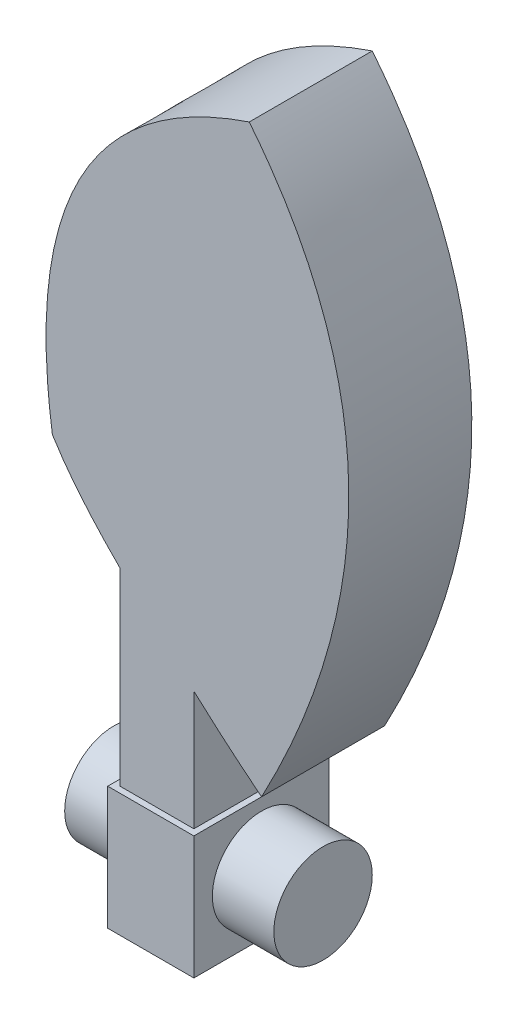
SolidWorks part; units mm, degrees
ref_plane "Front Plane" through (0, 0, 0) normal (0, 0, 1) x (1, 0, 0)
ref_plane "Top Plane" through (0, 0, 0) normal (0, 1, 0) x (1, 0, 0)
ref_plane "Right Plane" through (0, 0, 0) normal (1, 0, 0) x (0, 0, -1)
sketch "Sketch1" plane through (0, 0, 0) normal (0, 0, 1) x (1, 0, 0)
  spline S0 degree 2 poles (0, 0) (-3.4196, 23.4679) (16, 30) knots 0 0 0 1 1 1
  spline S1 degree 2 poles (16, 30) (31.6649, 10.4933) (17, -17) knots 0 0 0 1 1 1
  spline S2 degree 3 poles (0, 0) (2.2841, -3.7298) (8.7796, -9.7925) (13.5207, -14.2233) (17, -17) knots 0 0 0 0 0.559197 1 1 1 1
  dimension "D1" = 6
  dimension "D2" = 3
  dimension "D3" = 8
  dimension "D4" = 4
  dimension "D5" = 6
  dimension "D6" = 7
  dimension "D7" = 5.8243
  dimension "D8" = 16
  dimension "D9" = 20
  dimension "D10" = 24
  dimension "D11" = 30
extrude "Boss-Extrude1" add sketch "Sketch1" along normal blind 10
ref_plane "Plane2" through (0, -32, 0) normal (0, 1, 0) x (1, 0, 0)
sketch "Sketch5" plane through (0, -32, 0) normal (0, 1, 0) x (1, 0, 0)
  line L0 (5.5, -10) -> (11.5, -10)
  line L1 (0, -10) -> (17, -10) construction
  line L2 (11.5, -10) -> (11.5, 0)
  line L3 (17, 0) -> (0, 0) construction
  line L4 (11.5, 0) -> (5.5, 0)
  line L5 (5.5, 0) -> (5.5, -10)
  line L7 (17, -10) -> (17, 0) construction
  point P10 (8.5, -10)
  dimension "D1" = 6
  dimension "D3" = 8.5
extrude "Boss-Extrude3" add sketch "Sketch5" along normal up to next
sketch "Sketch6" plane through (0, -32, 0) normal (0, 1, 0) x (1, 0, 0)
  line L0 (11.5, -10) -> (11.5, 0) construction
  line L1 (5, -10.5) -> (12, -10.5)
  line L2 (5, -10.5) -> (5, 0.5)
  line L3 (5, 0.5) -> (12, 0.5)
  line L4 (12, -10.5) -> (12, 0.5)
  line L5 (5.5, 0) -> (5.5, -10) construction
  line L6 (5.5, -10) -> (11.5, -10) construction
  line L7 (11.5, 0) -> (5.5, 0) construction
  dimension "D1" = 0.5
  dimension "D2" = 0.5
  dimension "D3" = 0.5
  dimension "D4" = 0.5
extrude "Boss-Extrude4" add sketch "Sketch6" along normal blind 10
sketch "Sketch7" plane through (12, 0, 0) normal (1, 0, 0) x (0, 0, -1)
  line L0 (0.5, -22) -> (0.5, -32) construction
  line L1 (-10.5, -22) -> (0.5, -22) construction
  circle A0 centre (-5, -27) radius 4
  point P5 (0.5, -27)
  point P9 (-5, -22)
  dimension "D1" = 8
extrude "Boss-Extrude5" add sketch "Sketch7" along normal blind 5
sketch "Sketch8" plane through (5, 0, 0) normal (-1, 0, 0) x (0, 0, 1)
  line L0 (10.5, -22) -> (10.5, -32) construction
  line L1 (10, -22) -> (0, -22) construction
  circle A0 centre (5, -27) radius 4
  point P5 (10.5, -27)
  point P9 (5, -22)
  dimension "D1" = 8
extrude "Boss-Extrude6" add sketch "Sketch8" along normal blind 5
ref_plane "Plane10" through (5, -32, 10.5) normal (0, -1, 0) x (-1, 0, 0)
ref_plane "Plane11" through (0, -22, 0) normal (0, 1, 0) x (1, 0, 0)
split "Split1" trim tools "Plane11" bodies to split 107 resulting bodies 108 109
